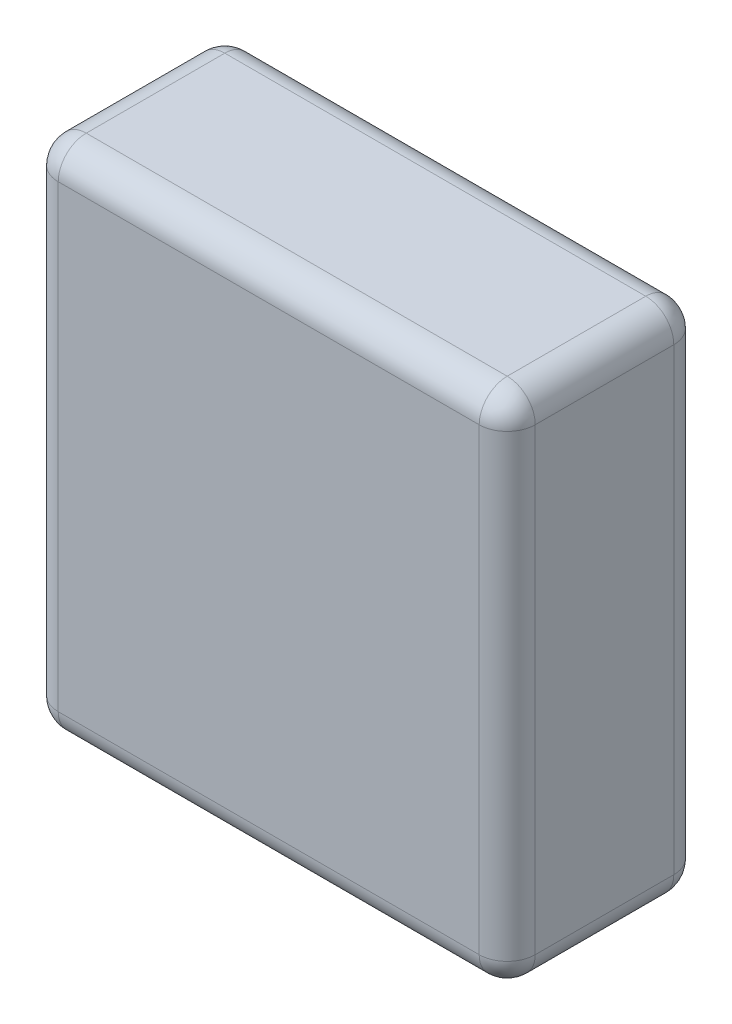
SolidWorks part; units mm, degrees
ref_plane "Front Plane" through (0, 0, 0) normal (0, 0, 1) x (1, 0, 0)
ref_plane "Top Plane" through (0, 0, 0) normal (0, 1, 0) x (1, 0, 0)
ref_plane "Right Plane" through (0, 0, 0) normal (1, 0, 0) x (0, 0, -1)
sketch "Sketch1" plane through (0, 0, 0) normal (0, 0, 1) x (1, 0, 0)
  line L1 (0, 0) -> (51.054, 0)
  line L2 (0, 0) -> (0, 55.118)
  line L3 (0, 55.118) -> (51.054, 55.118)
  line L4 (51.054, 0) -> (51.054, 55.118)
  dimension "D1" = 51.054
  dimension "D2" = 55.118
extrude "Boss-Extrude1" add sketch "Sketch1" along normal blind 20.828
fillet "Fillet1" radius 3 12 edges at (25.527, 0, 0) (0, 0, 10.414) (0, 27.559, 0) (51.054, 0, 10.414) (51.054, 27.559, 0) (51.054, 27.559, 20.828) (25.527, 0, 20.828) (0, 27.559, 20.828) (51.054, 55.118, 10.414) (25.527, 55.118, 20.828) (0, 55.118, 10.414) (25.527, 55.118, 0)
